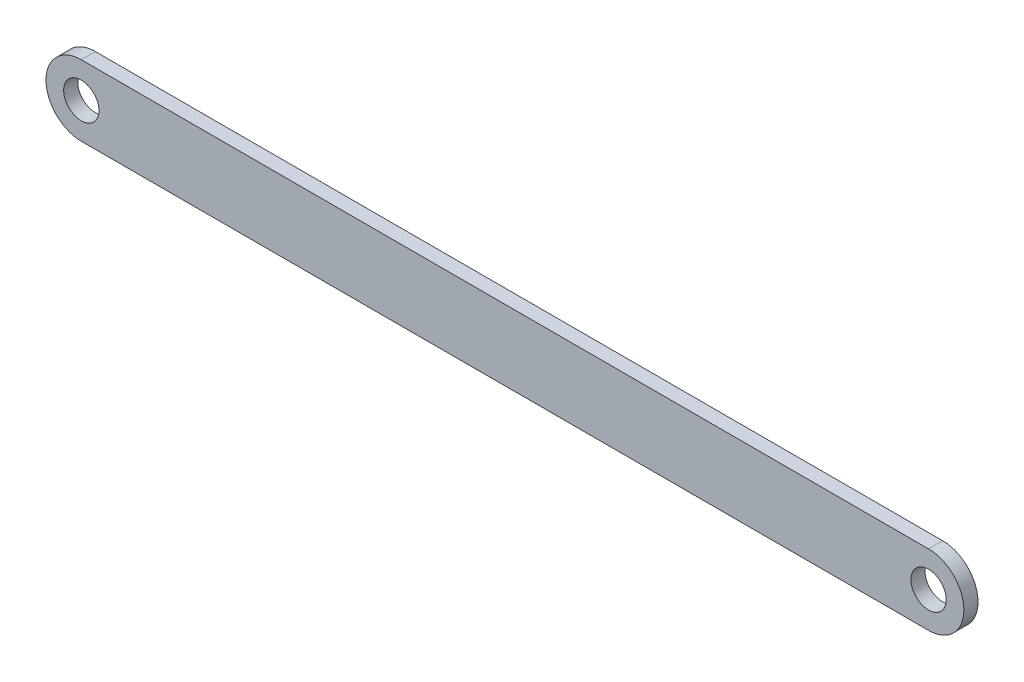
SolidWorks part; units mm, degrees
material "AISI 1020"
ref_plane "Front Plane" through (0, 0, 0) normal (0, 0, 1) x (1, 0, 0)
ref_plane "Top Plane" through (0, 0, 0) normal (0, 1, 0) x (1, 0, 0)
ref_plane "Right Plane" through (0, 0, 0) normal (1, 0, 0) x (0, 0, -1)
sketch "Sketch1" plane through (0, 0, 0) normal (0, 0, 1) x (1, 0, 0)
  line L0 (-36.1579, 8.7567) -> (-36.1579, -3.9433) construction
  line L1 (116.2421, 8.7567) -> (-36.1579, 8.7567)
  line L3 (116.2421, -3.9433) -> (-36.1579, -3.9433)
  line L5 (116.2421, 8.7567) -> (116.2421, -3.9433) construction
  arc A0 (-36.1579, 8.7567) -> (-36.1579, -3.9433) centre (-36.1579, 2.4067) ccw
  arc A1 (116.2421, 8.7567) -> (116.2421, -3.9433) centre (116.2421, 2.4067) cw
  circle A2 centre (-36.1579, 2.4067) radius 3.175
  circle A3 centre (116.2421, 2.4067) radius 3.175
  point P0 (0, 0)
  dimension "D1" = 6.35
  dimension "D2" = 152.4
  dimension "D3" = 6.35
  dimension "D4" = 12.7
extrude "Boss-Extrude1" add sketch "Sketch1" against normal blind 2.54
